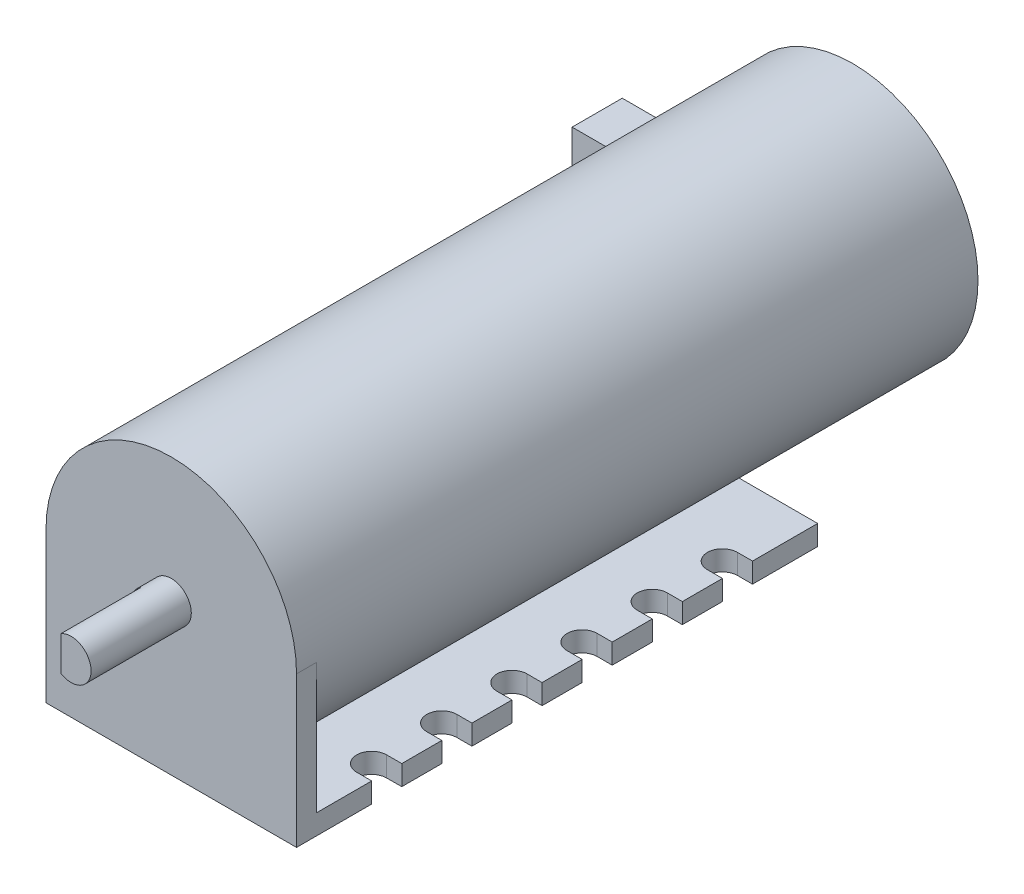
SolidWorks part; units mm, degrees
ref_plane "Front Plane" through (0, 0, 0) normal (0, 0, 1) x (1, 0, 0)
ref_plane "Top Plane" through (0, 0, 0) normal (0, 1, 0) x (1, 0, 0)
ref_plane "Right Plane" through (0, 0, 0) normal (1, 0, 0) x (0, 0, -1)
sketch "Sketch1" plane through (0, 0, 0) normal (0, 0, 1) x (1, 0, 0)
  circle A0 centre (0, 0) radius 12.5
  dimension "D1" = 25
extrude "Boss-Extrude1" add sketch "Sketch1" against normal blind 68
sketch "Sketch3" plane through (0, 0, 0) normal (0, 0, 1) x (1, 0, 0)
  circle A0 centre (0, 0) radius 2
  dimension "D1" = 4
extrude "Boss-Extrude3" add sketch "Sketch3" along normal blind 2
sketch "Sketch2" plane through (0, 0, 2) normal (0, 0, 1) x (1, 0, 0)
  line L0 (-1, 1.7321) -> (-1, -1.7321)
  arc A0 (-1, -1.7321) -> (-1, 1.7321) centre (0, 0) ccw
  dimension "D1" = 2
  dimension "D2" = 1
extrude "Boss-Extrude2" add sketch "Sketch2" along normal blind 8
sketch "Sketch4" plane through (0, 0, 0) normal (0, 0, 1) x (1, 0, 0)
  line L0 (-12.5, 0) -> (-12.5, -15)
  line L1 (-12.5, -15) -> (12.5, -15)
  line L2 (12.5, -15) -> (12.5, 0)
  circle A0 centre (0, 0) radius 12.5 construction
  arc A1 (-12.5, 0) -> (12.5, 0) centre (0, 0) ccw
  point P4 (0, -15)
  dimension "D1" = 15
extrude "Boss-Extrude4" add sketch "Sketch4" against normal blind 2
sketch "Sketch5" plane through (0, 0, -2) normal (0, 0, -1) x (-1, 0, 0)
  line L0 (-12.5, -13) -> (12.5, -13)
  line L1 (-12.5, -15) -> (-12.5, 0) construction
  line L2 (12.5, 0) -> (12.5, -15) construction
  line L3 (12.5, -13) -> (12.5, -15)
  line L4 (12.5, -15) -> (-12.5, -15)
  line L5 (-12.5, -15) -> (-12.5, -13)
  dimension "D1" = 2
extrude "Boss-Extrude5" add sketch "Sketch5" along normal blind 50
sketch "Sketch6" plane through (0, -15, 0) normal (0, -1, 0) x (1, 0, 0)
  line L0 (-12.5, 0) -> (12.5, 0) construction
  line L1 (12.5, -52) -> (-12.5, -52) construction
  line L2 (0, 0) -> (0, -52) construction
  line L3 (-11, -7.5) -> (-12.5, -7.5)
  line L4 (-12.5, -52) -> (-12.5, 0) construction
  line L5 (-11, -14.5) -> (-12.5, -14.5)
  line L6 (-11, -10.5) -> (-12.5, -10.5)
  line L7 (-11, -17.5) -> (-12.5, -17.5)
  line L8 (-11, -21.5) -> (-12.5, -21.5)
  line L9 (-11, -24.5) -> (-12.5, -24.5)
  line L10 (-11, -28.5) -> (-12.5, -28.5)
  line L11 (-11, -31.5) -> (-12.5, -31.5)
  line L12 (-11, -35.5) -> (-12.5, -35.5)
  line L13 (-11, -38.5) -> (-12.5, -38.5)
  line L14 (-11, -42.5) -> (-12.5, -42.5)
  line L15 (-11, -45.5) -> (-12.5, -45.5)
  line L16 (11, -45.5) -> (12.5, -45.5)
  line L17 (11, -42.5) -> (12.5, -42.5)
  line L18 (11, -38.5) -> (12.5, -38.5)
  line L19 (11, -35.5) -> (12.5, -35.5)
  line L20 (11, -31.5) -> (12.5, -31.5)
  line L21 (11, -28.5) -> (12.5, -28.5)
  line L22 (11, -24.5) -> (12.5, -24.5)
  line L23 (11, -21.5) -> (12.5, -21.5)
  line L24 (11, -17.5) -> (12.5, -17.5)
  line L25 (11, -14.5) -> (12.5, -14.5)
  line L26 (11, -7.5) -> (12.5, -7.5)
  line L27 (11, -10.5) -> (12.5, -10.5)
  line L28 (-12.5, -7.5) -> (-12.5, -10.5)
  line L29 (12.5, -7.5) -> (12.5, -10.5)
  line L30 (-12.5, -14.5) -> (-12.5, -17.5)
  line L31 (12.5, -45.5) -> (12.5, -42.5)
  line L32 (-12.5, -21.5) -> (-12.5, -24.5)
  line L33 (-12.5, -28.5) -> (-12.5, -31.5)
  line L34 (-12.5, -35.5) -> (-12.5, -38.5)
  line L35 (-12.5, -42.5) -> (-12.5, -45.5)
  line L36 (12.5, -38.5) -> (12.5, -35.5)
  line L37 (12.5, -31.5) -> (12.5, -28.5)
  line L38 (12.5, -24.5) -> (12.5, -21.5)
  line L39 (12.5, -17.5) -> (12.5, -14.5)
  circle A0 centre (0, -6) radius 1.5
  circle A1 centre (0, -12.5) radius 1.5
  circle A2 centre (0, -19) radius 1.5
  circle A3 centre (0, -25.5) radius 1.5
  circle A4 centre (0, -32) radius 1.5
  circle A5 centre (0, -38.5) radius 1.5
  circle A6 centre (0, -45) radius 1.5
  arc A7 (-11, -10.5) -> (-11, -7.5) centre (-11, -9) ccw
  arc A8 (-11, -17.5) -> (-11, -14.5) centre (-11, -16) ccw
  arc A9 (-11, -24.5) -> (-11, -21.5) centre (-11, -23) ccw
  arc A10 (-11, -31.5) -> (-11, -28.5) centre (-11, -30) ccw
  arc A11 (-11, -38.5) -> (-11, -35.5) centre (-11, -37) ccw
  arc A12 (-11, -45.5) -> (-11, -42.5) centre (-11, -44) ccw
  arc A13 (11, -45.5) -> (11, -42.5) centre (11, -44) cw
  arc A14 (11, -38.5) -> (11, -35.5) centre (11, -37) cw
  arc A15 (11, -31.5) -> (11, -28.5) centre (11, -30) cw
  arc A16 (11, -24.5) -> (11, -21.5) centre (11, -23) cw
  arc A17 (11, -17.5) -> (11, -14.5) centre (11, -16) cw
  arc A18 (11, -10.5) -> (11, -7.5) centre (11, -9) cw
  dimension "D2" = 3
  dimension "D5" = 1.5
  dimension "D3" = 6.5
  dimension "D4" = 6
  dimension "D6" = 1.5
  dimension "D7" = 9
  dimension "D9" = 7
  dimension "D1" = 7
  dimension "D8" = 6
extrude "Cut-Extrude1" cut sketch "Sketch6" against normal blind 2
sketch "Sketch7" plane through (0, 0, 0) normal (1, 0, 0) x (0, 0, -1)
  line L0 (68, -12.5) -> (68, 12.5) construction
  line L1 (60, 6) -> (55, 6)
  line L2 (60, 6) -> (60, -6)
  line L3 (60, -6) -> (55, -6)
  line L4 (55, 6) -> (55, -6)
  point P4 (60, 0)
  dimension "D1" = 12
  dimension "D2" = 5
  dimension "D3" = 8
extrude "Boss-Extrude6" add sketch "Sketch7" against normal blind 15
